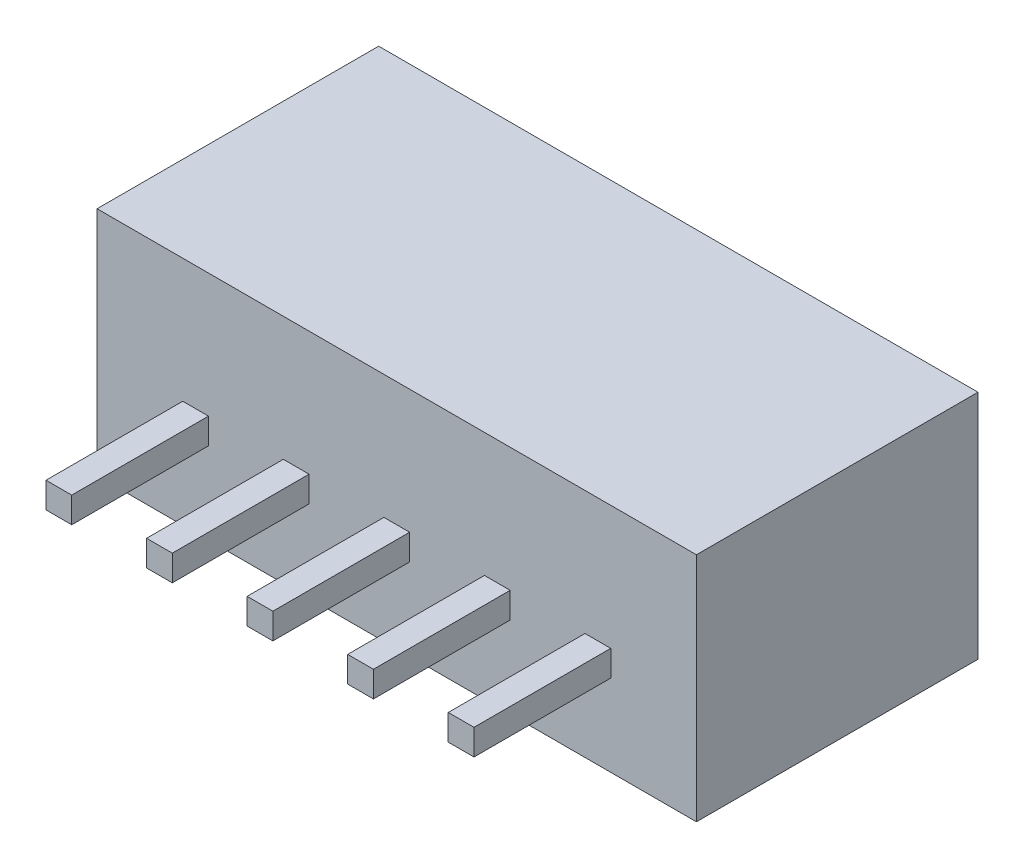
SolidWorks part; units mm, degrees
ref_plane "Спереди" through (0, 0, 0) normal (0, 0, 1) x (1, 0, 0)
ref_plane "Сверху" through (0, 0, 0) normal (0, 1, 0) x (1, 0, 0)
ref_plane "Справа" through (0, 0, 0) normal (1, 0, 0) x (0, 0, -1)
sketch "Эскиз1" plane through (0, 0, 0) normal (0, 0, 1) x (1, 0, 0)
  line L1 (-7.45, 2.875) -> (7.45, 2.875)
  line L2 (-7.45, 2.875) -> (-7.45, -2.875)
  line L3 (-7.45, -2.875) -> (7.45, -2.875)
  line L4 (7.45, 2.875) -> (7.45, -2.875)
  line L5 (-7.45, 2.875) -> (7.45, -2.875) construction
  line L6 (-7.45, -2.875) -> (7.45, 2.875) construction
  point P0 (0, 0)
  dimension "D1" = 5.75
  dimension "D2" = 14.9
extrude "Бобышка-Вытянуть1" add sketch "Эскиз1" along normal blind 7
sketch "Эскиз2" plane through (0, 0, 7) normal (0, 0, 1) x (1, 0, 0)
  line L0 (-2.82, -0.205) -> (-2.18, -0.205)
  line L1 (-5.32, -0.205) -> (-4.68, -0.205)
  line L2 (-5.32, -0.205) -> (-5.32, -0.845)
  line L3 (-5.32, -0.845) -> (-4.68, -0.845)
  line L4 (-4.68, -0.205) -> (-4.68, -0.845)
  line L5 (-5.32, -0.205) -> (-4.68, -0.845) construction
  line L6 (-5.32, -0.845) -> (-4.68, -0.205) construction
  line L7 (-2.82, -0.205) -> (-2.82, -0.845)
  line L8 (-2.82, -0.845) -> (-2.18, -0.845)
  line L9 (-2.18, -0.205) -> (-2.18, -0.845)
  line L10 (-2.82, -0.205) -> (-2.18, -0.845) construction
  line L11 (-2.82, -0.845) -> (-2.18, -0.205) construction
  line L12 (-0.32, -0.205) -> (0.32, -0.205)
  line L13 (-0.32, -0.205) -> (-0.32, -0.845)
  line L14 (-0.32, -0.845) -> (0.32, -0.845)
  line L15 (0.32, -0.205) -> (0.32, -0.845)
  line L16 (-0.32, -0.205) -> (0.32, -0.845) construction
  line L17 (-0.32, -0.845) -> (0.32, -0.205) construction
  line L18 (2.18, -0.205) -> (2.82, -0.205)
  line L19 (2.18, -0.205) -> (2.18, -0.845)
  line L20 (2.18, -0.845) -> (2.82, -0.845)
  line L21 (2.82, -0.205) -> (2.82, -0.845)
  line L22 (2.18, -0.205) -> (2.82, -0.845) construction
  line L23 (2.18, -0.845) -> (2.82, -0.205) construction
  line L24 (4.68, -0.205) -> (5.32, -0.205)
  line L25 (4.68, -0.205) -> (4.68, -0.845)
  line L26 (4.68, -0.845) -> (5.32, -0.845)
  line L27 (5.32, -0.205) -> (5.32, -0.845)
  line L28 (4.68, -0.205) -> (5.32, -0.845) construction
  line L29 (4.68, -0.845) -> (5.32, -0.205) construction
  line L30 (-7.45, -2.875) -> (7.45, -2.875) construction
  point P0 (-5, -0.525)
  point P5 (0, -0.205)
  point P6 (-2.5, -0.525)
  point P11 (0, -0.525)
  point P16 (2.5, -0.525)
  point P21 (5, -0.525)
  dimension "D1" = 0.64
  dimension "D2" = 5
  dimension "D3" = 2.35
extrude "Бобышка-Вытянуть2" add sketch "Эскиз2" along normal blind 3.4
sketch "Эскиз3" plane through (0, 0, 0) normal (0, 0, -1) x (-1, 0, 0)
  line L8 (-6.45, 1.875) -> (-6.45, -1.875)
  line L9 (-6.45, -1.875) -> (6.45, -1.875)
  line L10 (6.45, -1.875) -> (6.45, 1.875)
  line L11 (6.45, 1.875) -> (-6.45, 1.875)
  line L12 (-6.45, 1.875) -> (-6.45, -1.875)
  line L13 (-6.45, -1.875) -> (6.45, -1.875)
  line L14 (6.45, -1.875) -> (6.45, 1.875)
  line L15 (6.45, 1.875) -> (-6.45, 1.875)
  dimension "D1" = 1
extrude "Вырез-Вытянуть1" cut sketch "Эскиз3" against normal blind 5
